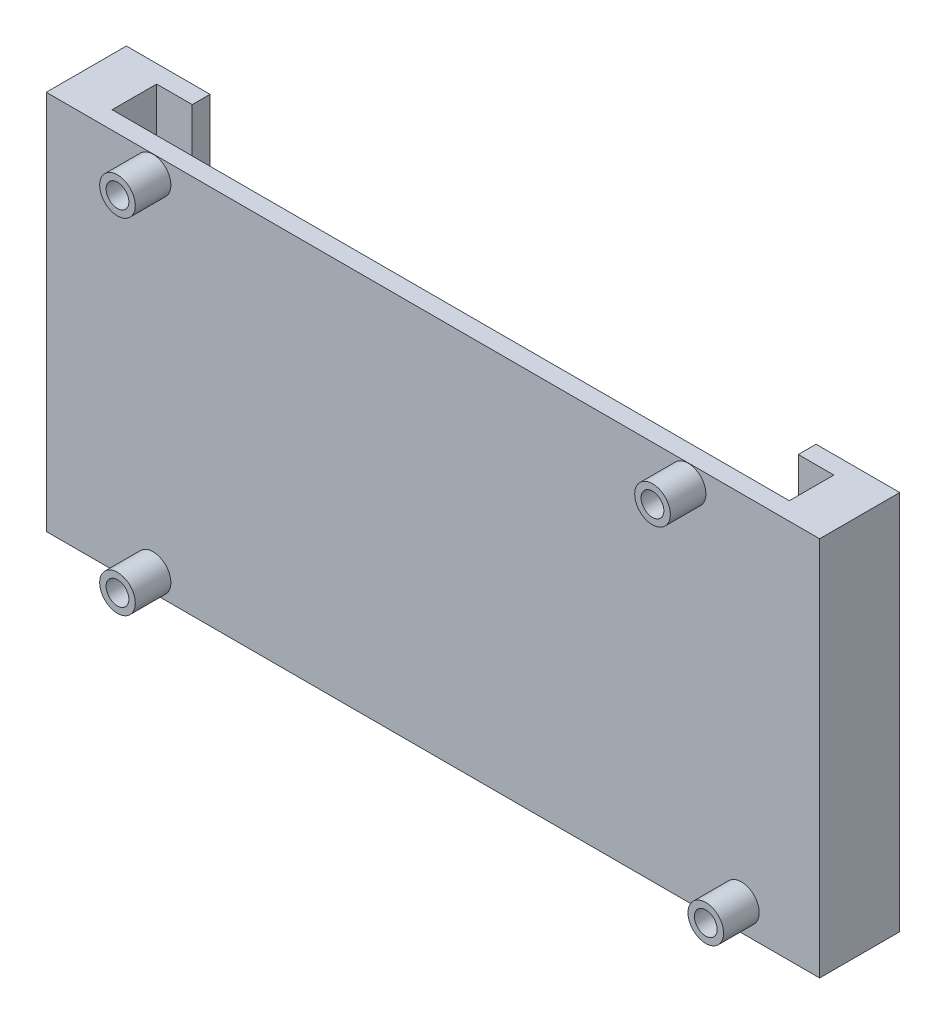
SolidWorks part; units mm, degrees
ref_plane "Front Plane" through (0, 0, 0) normal (0, 0, 1) x (1, 0, 0)
ref_plane "Top Plane" through (0, 0, 0) normal (0, 1, 0) x (1, 0, 0)
ref_plane "Right Plane" through (0, 0, 0) normal (1, 0, 0) x (0, 0, -1)
sketch "Sketch1" plane through (0, 0, 0) normal (0, 0, 1) x (1, 0, 0)
  line L1 (-54.3, -26.7081) -> (54.3, -26.7081)
  line L2 (-54.3, -26.7081) -> (-54.3, 26.7081)
  line L3 (-54.3, 26.7081) -> (54.3, 26.7081)
  line L4 (54.3, -26.7081) -> (54.3, 26.7081)
  line L5 (-54.3, -26.7081) -> (54.3, 26.7081) construction
  line L6 (-54.3, 26.7081) -> (54.3, -26.7081) construction
  point P0 (0, 0)
  dimension "D1" = 108.6
  dimension "D2" = 53.4162
extrude "Boss-Extrude1" add sketch "Sketch1" along normal blind 2.5
sketch "Sketch2" plane through (0, 0, 2.5) normal (0, 0, 1) x (1, 0, 0)
  line L0 (-54.3, 26.7081) -> (-54.3, -26.7081) construction
  line L1 (54.3, 26.7081) -> (-54.3, 26.7081) construction
  line L2 (-54.3, -26.7081) -> (54.3, -26.7081) construction
  circle A0 centre (-39.3, 24.1681) radius 2.5
  circle A1 centre (35.83, 24.1681) radius 2.5
  circle A2 centre (43.3119, -23.0081) radius 2.5
  circle A3 centre (-39.3, -24.1681) radius 2.5
  point P4 (0, 0)
  point P15 (0, 0)
  dimension "D3" = 5
  dimension "D4" = 75.13
  dimension "D5" = 47.1762
  dimension "D6" = 15
  dimension "D2" = 2.54
  dimension "D7" = 82.62
  dimension "D8" = 2.54
extrude "Boss-Extrude2" add sketch "Sketch2" along normal blind 5
sketch "Sketch3" plane through (0, 0, 7.5) normal (0, 0, 1) x (1, 0, 0)
  circle A0 centre (35.83, 24.1681) radius 2.5 construction
  point P0 (-39.3, 24.1681)
  point P3 (35.83, 24.1681)
  point P5 (43.3119, -23.0081)
  point P8 (-39.3, -24.1681)
  point P12 (0, 0)
hole_wizard "M3 Clearance Hole1" positions "Sketch3" profile "Sketch4" hole size "M3" standard "ANSI Metric" end condition through all
sketch "Sketch4" plane through (-39.3, 24.1681, 7.5) normal (1, 0, 0) x (0, -1, 0)
  line L0 (0, 0) -> (0, 7.5)
  line L1 (0, 7.5) -> (1.6, 7.5)
  line L2 (1.6, 7.5) -> (1.6, 0)
  line L5 (1.6, 0) -> (0, 0)
  line L11 (0, -6.35) -> (0, 107.95) construction
  dimension "Thru Hole Dia." = 3.2
  dimension "Thru Hole Depth" = 7.5
sketch "Sketch5" plane through (0, 0, 0) normal (0, 0, -1) x (-1, 0, 0)
  line L0 (54.3, -26.7081) -> (-54.3, -26.7081) construction
  line L1 (-54.3, 26.7081) -> (-47.55, 26.7081)
  line L2 (-54.3, 26.7081) -> (-54.3, -26.7081)
  line L3 (-54.3, -26.7081) -> (-47.55, -26.7081)
  line L4 (-47.55, 26.7081) -> (-47.55, -26.7081)
  line L6 (54.3, 26.7081) -> (47.55, 26.7081)
  line L7 (54.3, 26.7081) -> (54.3, -26.7081)
  line L8 (54.3, -26.7081) -> (47.55, -26.7081)
  line L9 (47.55, 26.7081) -> (47.55, -26.7081)
  dimension "D1" = 6.75
  dimension "D2" = 6.75
extrude "Boss-Extrude3" add sketch "Sketch5" along normal blind 8.75
sketch "Sketch6" plane through (47.55, 0, 0) normal (-1, 0, 0) x (0, 0, 1)
  line L0 (2.5, -26.7081) -> (-8.75, -26.7081) construction
  line L1 (-8.75, 26.7081) -> (-6.25, 26.7081)
  line L2 (-8.75, 26.7081) -> (-8.75, -26.7081)
  line L3 (-8.75, -26.7081) -> (-6.25, -26.7081)
  line L4 (-6.25, 26.7081) -> (-6.25, -26.7081)
  dimension "D1" = 2.5
extrude "Boss-Extrude4" add sketch "Sketch6" along normal blind 5
sketch "Sketch7" plane through (-47.55, 0, 0) normal (1, 0, 0) x (0, 0, -1)
  line L0 (-2.5, -26.7081) -> (8.75, -26.7081) construction
  line L1 (8.75, 26.7081) -> (6.25, 26.7081)
  line L2 (8.75, 26.7081) -> (8.75, -26.7081)
  line L3 (8.75, -26.7081) -> (6.25, -26.7081)
  line L4 (6.25, 26.7081) -> (6.25, -26.7081)
  dimension "D1" = 2.5
extrude "Boss-Extrude5" add sketch "Sketch7" along normal blind 5
sketch "Sketch8" plane through (0, -26.7081, 0) normal (0, -1, 0) x (1, 0, 0)
  line L0 (-54.3, -3.125) -> (54.3, -3.125) construction
  line L1 (-54.3, 2.5) -> (-54.3, -8.75) construction
  line L2 (54.3, 2.5) -> (54.3, -8.75) construction
  line L3 (-47.55, 0) -> (-54.3, 0) construction
  line L4 (-50.925, 0) -> (-50.925, -8.75) construction
  line L5 (-42.55, -8.75) -> (-54.3, -8.75) construction
  line L6 (47.55, 0) -> (54.3, 0) construction
  line L7 (50.925, 0) -> (50.925, -8.75) construction
  line L8 (54.3, -8.75) -> (42.55, -8.75) construction
  circle A0 centre (-50.925, -3.125) radius 3.15
  circle A1 centre (50.925, -3.125) radius 3.15
  point P23 (0, 0)
  dimension "D1" = 6.3
extrude "Cut-Extrude1" cut sketch "Sketch8" against normal blind 2.7
